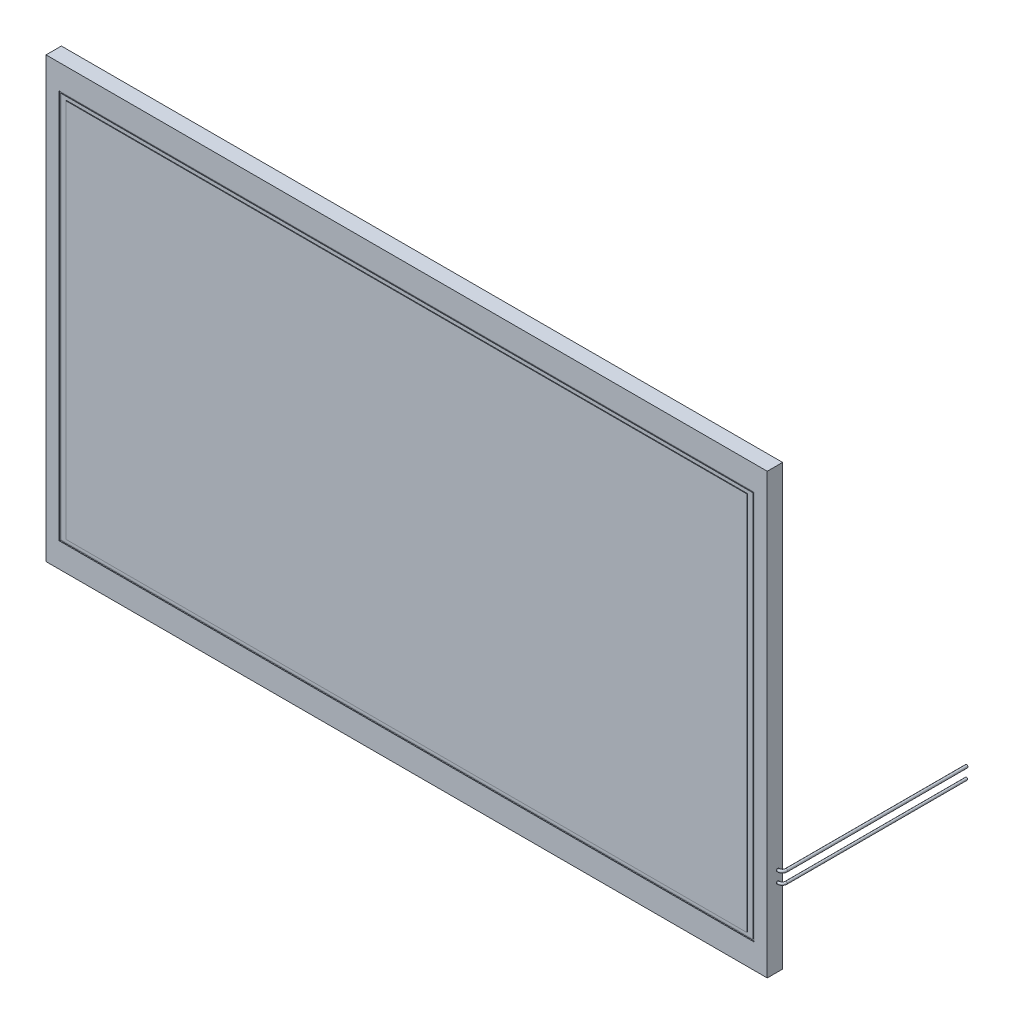
SolidWorks part; units mm, degrees
ref_plane "Front Plane" through (0, 0, 0) normal (0, 0, 1) x (1, 0, 0)
ref_plane "Top Plane" through (0, 0, 0) normal (0, 1, 0) x (1, 0, 0)
ref_plane "Right Plane" through (0, 0, 0) normal (1, 0, 0) x (0, 0, -1)
sketch "Sketch1" plane through (0, 0, 0) normal (0, 0, 1) x (1, 0, 0)
  line L1 (-117.5, -71.5) -> (117.5, -71.5)
  line L2 (-117.5, -71.5) -> (-117.5, 71.5)
  line L3 (-117.5, 71.5) -> (117.5, 71.5)
  line L4 (117.5, -71.5) -> (117.5, 71.5)
  line L5 (-117.5, -71.5) -> (117.5, 71.5) construction
  line L6 (-117.5, 71.5) -> (117.5, -71.5) construction
  point P0 (0, 0)
  dimension "D1" = 235
  dimension "D2" = 143
extrude "Boss-Extrude1" add sketch "Sketch1" against normal blind 5
sketch "Sketch2" plane through (0, 0, 0) normal (0, 0, 1) x (1, 0, 0)
  line L1 (-113.2, -63.49) -> (113.2, -63.49)
  line L2 (-113.2, -63.49) -> (-113.2, 63.49)
  line L3 (-113.2, 63.49) -> (113.2, 63.49)
  line L4 (113.2, -63.49) -> (113.2, 63.49)
  line L5 (-113.2, -63.49) -> (113.2, 63.49) construction
  line L6 (-113.2, 63.49) -> (113.2, -63.49) construction
  point P0 (0, 0)
  dimension "D1" = 226.4
  dimension "D2" = 126.98
extrude "Cut-Extrude1" cut sketch "Sketch2" against normal blind 0.3
sketch "Sketch3" plane through (0, 0, 0) normal (0, 0, 1) x (1, 0, 0)
  line L0 (113.2, 63.49) -> (-113.2, 63.49) construction
  line L1 (-112.7, -62.99) -> (112.7, -62.99)
  line L2 (-112.7, -62.99) -> (-112.7, 62.99)
  line L3 (-112.7, 62.99) -> (112.7, 62.99)
  line L4 (112.7, -62.99) -> (112.7, 62.99)
  line L5 (-112.7, -62.99) -> (112.7, 62.99) construction
  line L6 (-112.7, 62.99) -> (112.7, -62.99) construction
  line L7 (-113.2, 63.49) -> (-113.2, -63.49) construction
  line L8 (-110.95, 61.88) -> (-110.95, -61.88)
  line L9 (-110.95, 61.88) -> (110.95, 61.88)
  line L10 (110.95, 61.88) -> (110.95, -61.88)
  line L11 (110.95, -61.88) -> (-110.95, -61.88)
  point P0 (0, 0)
  dimension "D1" = 0.5
  dimension "D2" = 0.5
  dimension "D3" = 1.75
  dimension "D4" = 1.75
  dimension "D5" = 1.11
  dimension "D6" = 1.11
extrude "Boss-Extrude2" add sketch "Sketch3" along normal blind 0.2 from surface at -0.3 separate body contours L1 L4 L3 L2 L10 L11 L8 L9 starting at face at (0, 0, -0.3)
sketch "Sketch4" plane through (0, 0, -0.3) normal (0, 0, 1) x (1, 0, 0)
  line L1 (-110.95, -61.88) -> (110.95, -61.88)
  line L2 (-110.95, -61.88) -> (-110.95, 61.88)
  line L3 (-110.95, 61.88) -> (110.95, 61.88)
  line L4 (110.95, -61.88) -> (110.95, 61.88)
  line L5 (-110.95, -61.88) -> (110.95, 61.88) construction
  line L6 (-110.95, 61.88) -> (110.95, -61.88) construction
  point P0 (0, 0)
extrude "Boss-Extrude3" add sketch "Sketch4" along normal blind 0.2 from surface at 0.2 starting at face at (0, 0, -0.1)
sketch "Sketch5" plane through (0, 0, 0) normal (1, 0, 0) x (0, 0, -1)
  line L0 (1.2, -71.5) -> (1.2, -72)
  line L1 (5, -71.5) -> (0, -71.5) construction
  line L2 (0, 71.5) -> (0, -71.5) construction
  line L3 (2.2, -73) -> (69.2, -73)
  line L4 (1.3, -71.5) -> (1.3, -72)
  line L5 (2.2, -72.9) -> (69.2, -72.9)
  line L6 (1.2, -71.5) -> (1.3, -71.5)
  line L7 (69.2, -72.9) -> (69.2, -73)
  arc A0 (1.2, -72) -> (2.2, -73) centre (2.2, -72) ccw
  arc A1 (1.3, -72) -> (2.2, -72.9) centre (2.2, -72) ccw
  point P9 (1.2, -73)
  dimension "D3" = 1
  dimension "D5" = 67
  dimension "D1" = 1.2
  dimension "D2" = 1.5
  dimension "D4" = 0.1
extrude "Boss-Extrude4" add sketch "Sketch5" along normal blind 19.63 and the other way blind 18.67
sketch "Sketch7" plane through (0, -73, 0) normal (0, -1, 0) x (1, 0, 0)
  line L0 (-18.67, -29.3) -> (-12.27, -36.43)
  line L1 (-18.67, -2.2) -> (-18.67, -69.2) construction
  line L2 (-18.67, -2.2) -> (19.63, -2.2) construction
  line L3 (-12.27, -36.43) -> (-12.27, -69.2)
  line L4 (-18.67, -69.2) -> (19.63, -69.2) construction
  line L5 (-12.27, -69.2) -> (-18.67, -69.2)
  line L6 (-18.67, -69.2) -> (-18.67, -29.3)
  line L7 (0.48, 11.0885) -> (0.48, -8.894) construction
  line L8 (19.63, -69.2) -> (19.63, -29.3)
  line L9 (13.23, -69.2) -> (19.63, -69.2)
  line L10 (13.23, -36.43) -> (13.23, -69.2)
  line L11 (19.63, -29.3) -> (13.23, -36.43)
  point P18 (0.48, -2.2)
  dimension "D1" = 27.1
  dimension "D2" = 6.4
  dimension "D3" = 7.13
extrude "Cut-Extrude2" cut sketch "Sketch7" against normal blind 4.2
sketch "Sketch9" plane through (0, -73, 0) normal (0, -1, 0) x (1, 0, 0)
  line L0 (-12.27, -63.2) -> (-12.27, -69.2)
  line L1 (-12.27, -69.2) -> (-12.27, -36.43) construction
  line L2 (-12.27, -69.2) -> (13.23, -69.2)
  line L3 (13.23, -69.2) -> (13.23, -63.2)
  line L4 (13.23, -36.43) -> (13.23, -69.2) construction
  line L5 (13.23, -63.2) -> (-12.27, -63.2)
  dimension "D1" = 6
extrude "Boss-Extrude5" add sketch "Sketch9" against normal blind 0.3
sketch "Sketch8" plane through (0, -73, 0) normal (0, -1, 0) x (1, 0, 0)
  line L0 (-11.92, -69.2) -> (-11.92, -65.4)
  line L1 (-12.27, -69.2) -> (13.23, -69.2) construction
  line L3 (-11.62, -65.4) -> (-11.62, -69.2)
  line L4 (-11.92, -69.2) -> (-11.62, -69.2)
  line L5 (-12.27, -69.2) -> (-12.27, -36.43) construction
  line L6 (-11.92, -65.4) -> (-11.62, -65.4)
  line L7 (-11.42, -65.4) -> (-11.12, -65.4)
  line L8 (-11.42, -69.2) -> (-11.42, -65.4)
  line L9 (-11.12, -65.4) -> (-11.12, -69.2)
  line L10 (-11.42, -69.2) -> (-11.12, -69.2)
  line L11 (-10.92, -65.4) -> (-10.62, -65.4)
  line L12 (-10.92, -69.2) -> (-10.92, -65.4)
  line L13 (-10.62, -65.4) -> (-10.62, -69.2)
  line L14 (-10.92, -69.2) -> (-10.62, -69.2)
  line L15 (-10.42, -65.4) -> (-10.12, -65.4)
  line L16 (-10.42, -69.2) -> (-10.42, -65.4)
  line L17 (-10.12, -65.4) -> (-10.12, -69.2)
  line L18 (-10.42, -69.2) -> (-10.12, -69.2)
  line L19 (-9.92, -65.4) -> (-9.62, -65.4)
  line L20 (-9.92, -69.2) -> (-9.92, -65.4)
  line L21 (-9.62, -65.4) -> (-9.62, -69.2)
  line L22 (-9.92, -69.2) -> (-9.62, -69.2)
  line L23 (-9.42, -65.4) -> (-9.12, -65.4)
  line L24 (-9.42, -69.2) -> (-9.42, -65.4)
  line L25 (-9.12, -65.4) -> (-9.12, -69.2)
  line L26 (-9.42, -69.2) -> (-9.12, -69.2)
  line L27 (-8.92, -65.4) -> (-8.62, -65.4)
  line L28 (-8.92, -69.2) -> (-8.92, -65.4)
  line L29 (-8.62, -65.4) -> (-8.62, -69.2)
  line L30 (-8.92, -69.2) -> (-8.62, -69.2)
  line L31 (-8.42, -65.4) -> (-8.12, -65.4)
  line L32 (-8.42, -69.2) -> (-8.42, -65.4)
  line L33 (-8.12, -65.4) -> (-8.12, -69.2)
  line L34 (-8.42, -69.2) -> (-8.12, -69.2)
  line L35 (-7.92, -65.4) -> (-7.62, -65.4)
  line L36 (-7.92, -69.2) -> (-7.92, -65.4)
  line L37 (-7.62, -65.4) -> (-7.62, -69.2)
  line L38 (-7.92, -69.2) -> (-7.62, -69.2)
  line L39 (-7.42, -65.4) -> (-7.12, -65.4)
  line L40 (-7.42, -69.2) -> (-7.42, -65.4)
  line L41 (-7.12, -65.4) -> (-7.12, -69.2)
  line L42 (-7.42, -69.2) -> (-7.12, -69.2)
  line L43 (-6.92, -65.4) -> (-6.62, -65.4)
  line L44 (-6.92, -69.2) -> (-6.92, -65.4)
  line L45 (-6.62, -65.4) -> (-6.62, -69.2)
  line L46 (-6.92, -69.2) -> (-6.62, -69.2)
  line L47 (-6.42, -65.4) -> (-6.12, -65.4)
  line L48 (-6.42, -69.2) -> (-6.42, -65.4)
  line L49 (-6.12, -65.4) -> (-6.12, -69.2)
  line L50 (-6.42, -69.2) -> (-6.12, -69.2)
  line L51 (-5.92, -65.4) -> (-5.62, -65.4)
  line L52 (-5.92, -69.2) -> (-5.92, -65.4)
  line L53 (-5.62, -65.4) -> (-5.62, -69.2)
  line L54 (-5.92, -69.2) -> (-5.62, -69.2)
  line L55 (-5.42, -65.4) -> (-5.12, -65.4)
  line L56 (-5.42, -69.2) -> (-5.42, -65.4)
  line L57 (-5.12, -65.4) -> (-5.12, -69.2)
  line L58 (-5.42, -69.2) -> (-5.12, -69.2)
  line L59 (-4.92, -65.4) -> (-4.62, -65.4)
  line L60 (-4.92, -69.2) -> (-4.92, -65.4)
  line L61 (-4.62, -65.4) -> (-4.62, -69.2)
  line L62 (-4.92, -69.2) -> (-4.62, -69.2)
  line L63 (-4.42, -65.4) -> (-4.12, -65.4)
  line L64 (-4.42, -69.2) -> (-4.42, -65.4)
  line L65 (-4.12, -65.4) -> (-4.12, -69.2)
  line L66 (-4.42, -69.2) -> (-4.12, -69.2)
  line L67 (-3.92, -65.4) -> (-3.62, -65.4)
  line L68 (-3.92, -69.2) -> (-3.92, -65.4)
  line L69 (-3.62, -65.4) -> (-3.62, -69.2)
  line L70 (-3.92, -69.2) -> (-3.62, -69.2)
  line L71 (-3.42, -65.4) -> (-3.12, -65.4)
  line L72 (-3.42, -69.2) -> (-3.42, -65.4)
  line L73 (-3.12, -65.4) -> (-3.12, -69.2)
  line L74 (-3.42, -69.2) -> (-3.12, -69.2)
  line L75 (-2.92, -65.4) -> (-2.62, -65.4)
  line L76 (-2.92, -69.2) -> (-2.92, -65.4)
  line L77 (-2.62, -65.4) -> (-2.62, -69.2)
  line L78 (-2.92, -69.2) -> (-2.62, -69.2)
  line L79 (-2.42, -65.4) -> (-2.12, -65.4)
  line L80 (-2.42, -69.2) -> (-2.42, -65.4)
  line L81 (-2.12, -65.4) -> (-2.12, -69.2)
  line L82 (-2.42, -69.2) -> (-2.12, -69.2)
  line L83 (-1.92, -65.4) -> (-1.62, -65.4)
  line L84 (-1.92, -69.2) -> (-1.92, -65.4)
  line L85 (-1.62, -65.4) -> (-1.62, -69.2)
  line L86 (-1.92, -69.2) -> (-1.62, -69.2)
  line L87 (-1.42, -65.4) -> (-1.12, -65.4)
  line L88 (-1.42, -69.2) -> (-1.42, -65.4)
  line L89 (-1.12, -65.4) -> (-1.12, -69.2)
  line L90 (-1.42, -69.2) -> (-1.12, -69.2)
  line L91 (-0.92, -65.4) -> (-0.62, -65.4)
  line L92 (-0.92, -69.2) -> (-0.92, -65.4)
  line L93 (-0.62, -65.4) -> (-0.62, -69.2)
  line L94 (-0.92, -69.2) -> (-0.62, -69.2)
  line L95 (-0.42, -65.4) -> (-0.12, -65.4)
  line L96 (-0.42, -69.2) -> (-0.42, -65.4)
  line L97 (-0.12, -65.4) -> (-0.12, -69.2)
  line L98 (-0.42, -69.2) -> (-0.12, -69.2)
  line L99 (0.08, -65.4) -> (0.38, -65.4)
  line L100 (0.08, -69.2) -> (0.08, -65.4)
  line L101 (0.38, -65.4) -> (0.38, -69.2)
  line L102 (0.08, -69.2) -> (0.38, -69.2)
  line L103 (0.58, -65.4) -> (0.88, -65.4)
  line L104 (0.58, -69.2) -> (0.58, -65.4)
  line L105 (0.88, -65.4) -> (0.88, -69.2)
  line L106 (0.58, -69.2) -> (0.88, -69.2)
  line L107 (1.08, -65.4) -> (1.38, -65.4)
  line L108 (1.08, -69.2) -> (1.08, -65.4)
  line L109 (1.38, -65.4) -> (1.38, -69.2)
  line L110 (1.08, -69.2) -> (1.38, -69.2)
  line L111 (1.58, -65.4) -> (1.88, -65.4)
  line L112 (1.58, -69.2) -> (1.58, -65.4)
  line L113 (1.88, -65.4) -> (1.88, -69.2)
  line L114 (1.58, -69.2) -> (1.88, -69.2)
  line L115 (2.08, -65.4) -> (2.38, -65.4)
  line L116 (2.08, -69.2) -> (2.08, -65.4)
  line L117 (2.38, -65.4) -> (2.38, -69.2)
  line L118 (2.08, -69.2) -> (2.38, -69.2)
  line L119 (2.58, -65.4) -> (2.88, -65.4)
  line L120 (2.58, -69.2) -> (2.58, -65.4)
  line L121 (2.88, -65.4) -> (2.88, -69.2)
  line L122 (2.58, -69.2) -> (2.88, -69.2)
  line L123 (3.08, -65.4) -> (3.38, -65.4)
  line L124 (3.08, -69.2) -> (3.08, -65.4)
  line L125 (3.38, -65.4) -> (3.38, -69.2)
  line L126 (3.08, -69.2) -> (3.38, -69.2)
  line L127 (3.58, -65.4) -> (3.88, -65.4)
  line L128 (3.58, -69.2) -> (3.58, -65.4)
  line L129 (3.88, -65.4) -> (3.88, -69.2)
  line L130 (3.58, -69.2) -> (3.88, -69.2)
  line L131 (4.08, -65.4) -> (4.38, -65.4)
  line L132 (4.08, -69.2) -> (4.08, -65.4)
  line L133 (4.38, -65.4) -> (4.38, -69.2)
  line L134 (4.08, -69.2) -> (4.38, -69.2)
  line L135 (4.58, -65.4) -> (4.88, -65.4)
  line L136 (4.58, -69.2) -> (4.58, -65.4)
  line L137 (4.88, -65.4) -> (4.88, -69.2)
  line L138 (4.58, -69.2) -> (4.88, -69.2)
  line L139 (5.08, -65.4) -> (5.38, -65.4)
  line L140 (5.08, -69.2) -> (5.08, -65.4)
  line L141 (5.38, -65.4) -> (5.38, -69.2)
  line L142 (5.08, -69.2) -> (5.38, -69.2)
  line L143 (5.58, -65.4) -> (5.88, -65.4)
  line L144 (5.58, -69.2) -> (5.58, -65.4)
  line L145 (5.88, -65.4) -> (5.88, -69.2)
  line L146 (5.58, -69.2) -> (5.88, -69.2)
  line L147 (6.08, -65.4) -> (6.38, -65.4)
  line L148 (6.08, -69.2) -> (6.08, -65.4)
  line L149 (6.38, -65.4) -> (6.38, -69.2)
  line L150 (6.08, -69.2) -> (6.38, -69.2)
  line L151 (6.58, -65.4) -> (6.88, -65.4)
  line L152 (6.58, -69.2) -> (6.58, -65.4)
  line L153 (6.88, -65.4) -> (6.88, -69.2)
  line L154 (6.58, -69.2) -> (6.88, -69.2)
  line L155 (7.08, -65.4) -> (7.38, -65.4)
  line L156 (7.08, -69.2) -> (7.08, -65.4)
  line L157 (7.38, -65.4) -> (7.38, -69.2)
  line L158 (7.08, -69.2) -> (7.38, -69.2)
  line L159 (7.58, -65.4) -> (7.88, -65.4)
  line L160 (7.58, -69.2) -> (7.58, -65.4)
  line L161 (7.88, -65.4) -> (7.88, -69.2)
  line L162 (7.58, -69.2) -> (7.88, -69.2)
  line L163 (8.08, -65.4) -> (8.38, -65.4)
  line L164 (8.08, -69.2) -> (8.08, -65.4)
  line L165 (8.38, -65.4) -> (8.38, -69.2)
  line L166 (8.08, -69.2) -> (8.38, -69.2)
  line L167 (8.58, -65.4) -> (8.88, -65.4)
  line L168 (8.58, -69.2) -> (8.58, -65.4)
  line L169 (8.88, -65.4) -> (8.88, -69.2)
  line L170 (8.58, -69.2) -> (8.88, -69.2)
  line L171 (9.08, -65.4) -> (9.38, -65.4)
  line L172 (9.08, -69.2) -> (9.08, -65.4)
  line L173 (9.38, -65.4) -> (9.38, -69.2)
  line L174 (9.08, -69.2) -> (9.38, -69.2)
  line L175 (9.58, -65.4) -> (9.88, -65.4)
  line L176 (9.58, -69.2) -> (9.58, -65.4)
  line L177 (9.88, -65.4) -> (9.88, -69.2)
  line L178 (9.58, -69.2) -> (9.88, -69.2)
  line L179 (10.08, -65.4) -> (10.38, -65.4)
  line L180 (10.08, -69.2) -> (10.08, -65.4)
  line L181 (10.38, -65.4) -> (10.38, -69.2)
  line L182 (10.08, -69.2) -> (10.38, -69.2)
  line L183 (10.58, -65.4) -> (10.88, -65.4)
  line L184 (10.58, -69.2) -> (10.58, -65.4)
  line L185 (10.88, -65.4) -> (10.88, -69.2)
  line L186 (10.58, -69.2) -> (10.88, -69.2)
  line L187 (11.08, -65.4) -> (11.38, -65.4)
  line L188 (11.08, -69.2) -> (11.08, -65.4)
  line L189 (11.38, -65.4) -> (11.38, -69.2)
  line L190 (11.08, -69.2) -> (11.38, -69.2)
  line L191 (11.58, -65.4) -> (11.88, -65.4)
  line L192 (11.58, -69.2) -> (11.58, -65.4)
  line L193 (11.88, -65.4) -> (11.88, -69.2)
  line L194 (11.58, -69.2) -> (11.88, -69.2)
  line L195 (12.08, -65.4) -> (12.38, -65.4)
  line L196 (12.08, -69.2) -> (12.08, -65.4)
  line L197 (12.38, -65.4) -> (12.38, -69.2)
  line L198 (12.08, -69.2) -> (12.38, -69.2)
  line L199 (12.58, -65.4) -> (12.88, -65.4)
  line L200 (12.58, -69.2) -> (12.58, -65.4)
  line L201 (12.88, -65.4) -> (12.88, -69.2)
  line L202 (12.58, -69.2) -> (12.88, -69.2)
  dimension "D1" = 0.3
  dimension "D2" = 3.8
  dimension "D3" = 0.35
  dimension "D4" = 50
  dimension "D5" = 0.2
extrude "Cut-Extrude3" cut sketch "Sketch8" against normal blind 0.01
sketch "Sketch10" plane through (0, 0, 0) normal (1, 0, 0) x (0, 0, -1)
  line L4 (69.2, -72.7) -> (69.2, -73) construction
  line L7 (2.2, -73) -> (29.3, -73) construction
  line L8 (29.3, -72.9) -> (2.2, -72.9) construction
  line L9 (1.3, -72) -> (1.3, -71.5) construction
  line L10 (1.2, -71.5) -> (1.2, -72) construction
  line L11 (1.3, -71.5) -> (1.2, -71.5) construction
  line L12 (2.2, -73) -> (69.2, -73)
  line L13 (69.2, -72.9) -> (2.2, -72.9)
  line L14 (1.3, -72) -> (1.3, -71.5)
  line L15 (1.2, -71.5) -> (1.2, -72)
  line L16 (1.3, -71.5) -> (1.2, -71.5)
  line L17 (36.43, -73) -> (29.3, -73) construction
  line L18 (69.2, -72.9) -> (69.2, -73)
  arc A2 (1.2, -72) -> (2.2, -73) centre (2.2, -72) ccw construction
  arc A3 (1.3, -72) -> (2.2, -72.9) centre (2.2, -72) ccw construction
  arc A4 (1.2, -72) -> (2.2, -73) centre (2.2, -72) ccw
  arc A5 (1.3, -72) -> (2.2, -72.9) centre (2.2, -72) ccw
extrude "Boss-Extrude7" add sketch "Sketch10" against normal blind 12.256 from offset 30 offset against normal yes
sketch "Sketch11" plane through (0, -73, 0) normal (0, -1, 0) x (1, 0, 0)
  line L1 (-42.256, -2.2) -> (-42.256, -69.2) construction
  line L2 (-39.056, -5.2) -> (-39.056, -69.2)
  line L3 (-42.256, -69.2) -> (-30, -69.2) construction
  line L4 (-39.056, -69.2) -> (-42.256, -69.2)
  line L5 (-42.256, -69.2) -> (-42.256, -3.7)
  line L6 (-36.128, -2.2) -> (-36.128, -9.484) construction
  line L7 (-42.256, -2.2) -> (-30, -2.2) construction
  line L10 (-42.256, -3.7) -> (-40.556, -3.7)
  line L11 (-42.256, -1.2) -> (-30, -1.2) construction
  line L12 (-30, -3.7) -> (-31.7, -3.7)
  line L13 (-30, -69.2) -> (-30, -3.7)
  line L14 (-33.2, -69.2) -> (-30, -69.2)
  line L15 (-33.2, -5.2) -> (-33.2, -69.2)
  arc A0 (-40.556, -3.7) -> (-39.056, -5.2) centre (-40.556, -5.2) cw
  arc A1 (-31.7, -3.7) -> (-33.2, -5.2) centre (-31.7, -5.2) ccw
  point P15 (-39.056, -3.7)
  point P24 (-33.2, -3.7)
  dimension "D2" = 1.5
  dimension "D1" = 3.2
  dimension "D3" = 2.5
extrude "Cut-Extrude4" cut sketch "Sketch11" against normal up to next contours L5 L10 A0 L2 L4
sketch3d "3DSketch1"
  line L0 (117.5, -71.5, -5) -> (117.5, -71.5, 0) construction
  line L1 (117.5, -71.5, 0) -> (117.5, 71.5, 0) construction
  line L2 (117.5, -46.2, -3.4) -> (117.75, -46.2, -3.4)
  line L3 (119, -46.2, -4.65) -> (119, -46.2, -63.4)
  arc A0 (117.75, -46.2, -3.4) -> (119, -46.2, -4.65) centre (117.75, -46.2, -4.65) ccw
  point P0 (117.5, -46.2, -3.4)
  point P11 (119, -46.2, -3.4)
  point P12 (117.75, -44.95, -4.65)
  dimension "D5" = 1.25
  dimension "D2" = 3.4
  dimension "D1" = 25.3
  dimension "D4" = 1.5
  dimension "D3" = 60
sweep "Sweep1" add path "3DSketch1" circular profile diameter 0.8 parameters "D3"=0.8
sketch3d "3DSketch2"
  line L0 (117.5, -71.5, 0) -> (117.5, 71.5, 0) construction
  line L1 (117.5, -42.7004, -3.45) -> (117.75, -42.7004, -3.45)
  line L2 (119, -42.7004, -4.7) -> (119, -42.7004, -63.45)
  line L4 (117.5, -71.5, -5) -> (117.5, -71.5, 0) construction
  arc A1 (117.75, -42.7004, -3.45) -> (119, -42.7004, -4.7) centre (117.75, -42.7004, -4.7) ccw
  point P0 (117.5, -42.7004, -3.45)
  point P11 (119, -42.7004, -3.45)
  point P12 (117.75, -41.4504, -4.7)
  dimension "D5" = 1.25
  dimension "D1" = 3.45
  dimension "D2" = 28.7996
  dimension "D3" = 60
  dimension "D4" = 1.5
sweep "Sweep7" add path "3DSketch2" circular profile diameter 0.9 parameters "D3"=0.9
